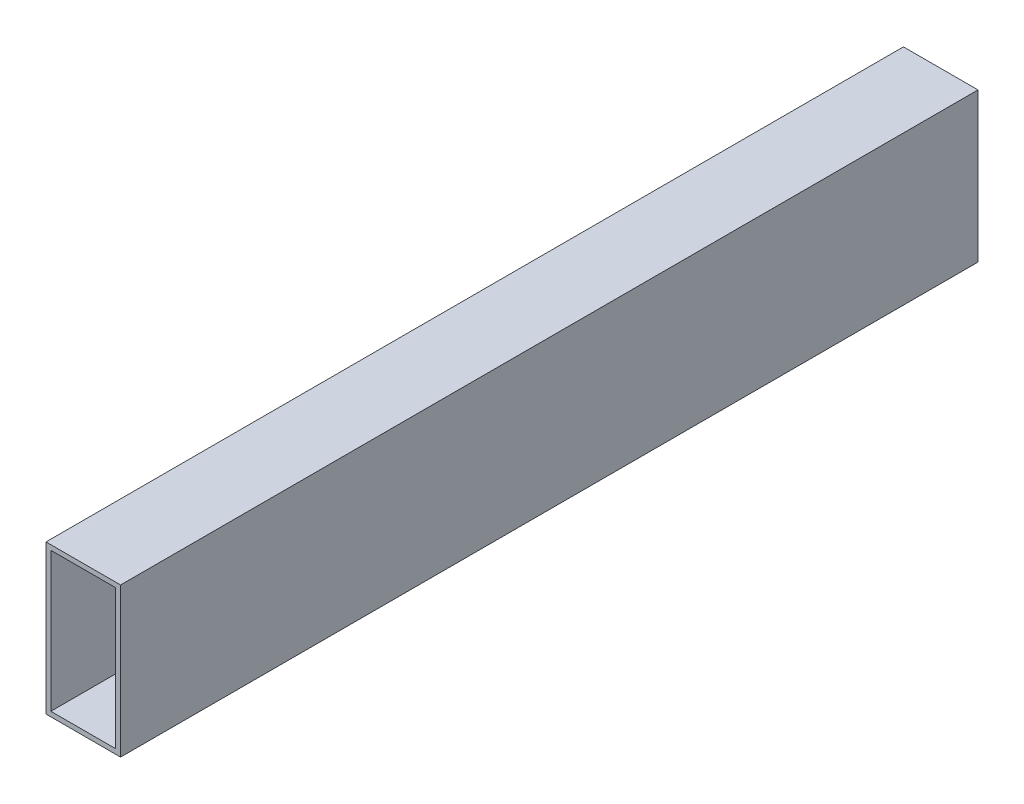
SolidWorks part; units mm, degrees
material "6061 Alloy"
ref_plane "Front Plane" through (0, 0, 0) normal (0, 0, 1) x (1, 0, 0)
ref_plane "Top Plane" through (0, 0, 0) normal (0, 1, 0) x (1, 0, 0)
ref_plane "Right Plane" through (0, 0, 0) normal (1, 0, 0) x (0, 0, -1)
sketch "Sketch1" plane through (0, 0, 0) normal (0, 0, 1) x (1, 0, 0)
  line L1 (-48.4372, -30.1994) -> (-23.0372, -30.1994)
  line L2 (-48.4372, -30.1994) -> (-48.4372, 20.6006)
  line L3 (-48.4372, 20.6006) -> (-23.0372, 20.6006)
  line L4 (-23.0372, -30.1994) -> (-23.0372, 20.6006)
  dimension "D1" = 25.4
  dimension "D2" = 50.8
extrude "Boss-Extrude1" add sketch "Sketch1" along normal blind 292.1
sketch "Sketch2" plane through (0, 0, 292.1) normal (0, 0, 1) x (1, 0, 0)
  line L0 (-48.4372, 20.6006) -> (-48.4372, -30.1994) construction
  line L1 (-46.7862, 18.9496) -> (-24.6882, 18.9496)
  line L2 (-46.7862, 18.9496) -> (-46.7862, -28.5484)
  line L3 (-46.7862, -28.5484) -> (-24.6882, -28.5484)
  line L4 (-24.6882, 18.9496) -> (-24.6882, -28.5484)
  line L5 (-46.7862, 18.9496) -> (-24.6882, -28.5484) construction
  line L6 (-46.7862, -28.5484) -> (-24.6882, 18.9496) construction
  line L7 (-23.0372, -30.1994) -> (-23.0372, 20.6006) construction
  line L8 (-23.0372, 20.6006) -> (-48.4372, 20.6006) construction
  line L9 (-48.4372, -30.1994) -> (-23.0372, -30.1994) construction
  point P0 (-35.7372, -4.7994)
  dimension "D1" = 1.651
  dimension "D2" = 1.651
  dimension "D3" = 1.651
  dimension "D4" = 1.651
extrude "Cut-Extrude1" cut sketch "Sketch2" against normal through all
ref_plane "mid plane" through (0, 0, 146.05) normal (0, 0, 1) x (1, 0, 0)
